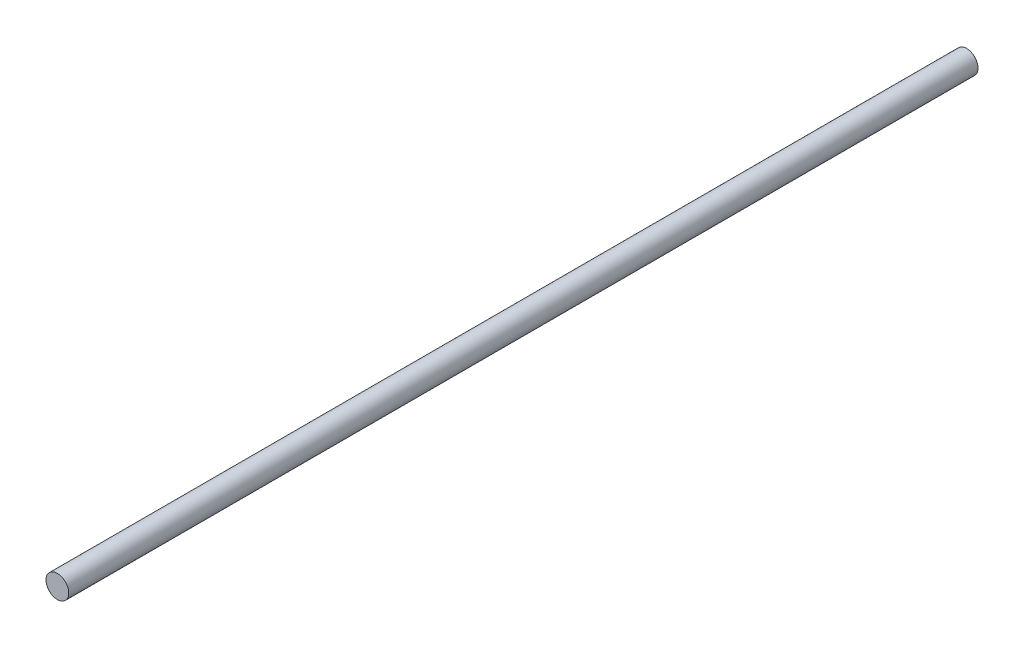
SolidWorks part; units mm, degrees
ref_plane "Front Plane" through (0, 0, 0) normal (0, 0, 1) x (1, 0, 0)
ref_plane "Top Plane" through (0, 0, 0) normal (0, 1, 0) x (1, 0, 0)
ref_plane "Right Plane" through (0, 0, 0) normal (1, 0, 0) x (0, 0, -1)
sketch "Sketch1" plane through (0, 0, 0) normal (0, 0, 1) x (1, 0, 0)
  circle A0 centre (0, 0) radius 3.81
  dimension "D1" = 7.62
extrude "Boss-Extrude1" add sketch "Sketch1" along normal blind 304.8
